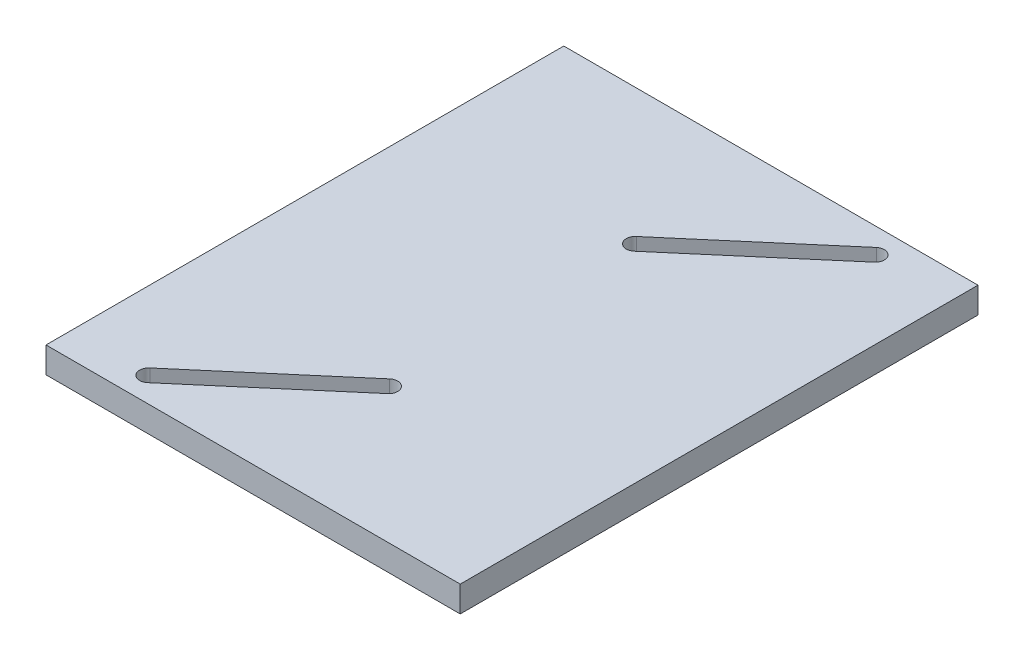
SolidWorks part; units mm, degrees
ref_plane "Front Plane" through (0, 0, 0) normal (0, 0, 1) x (1, 0, 0)
ref_plane "Top Plane" through (0, 0, 0) normal (0, 1, 0) x (1, 0, 0)
ref_plane "Right Plane" through (0, 0, 0) normal (1, 0, 0) x (0, 0, -1)
sketch "Sketch1" plane through (0, 0, 0) normal (0, 1, 0) x (1, 0, 0)
  line L1 (-50.8, -63.5) -> (50.8, -63.5)
  line L2 (-50.8, -63.5) -> (-50.8, 63.5)
  line L3 (-50.8, 63.5) -> (50.8, 63.5)
  line L4 (50.8, -63.5) -> (50.8, 63.5)
  line L5 (-50.8, -63.5) -> (50.8, 63.5) construction
  line L6 (-50.8, 63.5) -> (50.8, -63.5) construction
  point P0 (0, 0)
  dimension "D1" = 127
  dimension "D2" = 101.6
extrude "Boss-Extrude1" add sketch "Sketch1" along normal blind 6.35
sketch "Sketch2" plane through (0, 6.35, 0) normal (0, 1, 0) x (1, 0, 0)
  line L0 (0, 30.2489) -> (31.75, 57.3456) construction
  line L1 (-1.4428, 31.9394) -> (30.3072, 59.0361)
  line L2 (1.4428, 28.5583) -> (33.1928, 55.655)
  line L3 (50.8, 0) -> (-50.8, 0) construction
  line L4 (50.8, -63.5) -> (50.8, 63.5) construction
  line L5 (-50.8, 63.5) -> (-50.8, -63.5) construction
  line L6 (50.8, 63.5) -> (-50.8, 63.5) construction
  line L7 (0, 63.5) -> (0, -63.5) construction
  line L8 (-50.8, -63.5) -> (50.8, -63.5) construction
  line L12 (0, -30.2489) -> (-31.75, -57.3456) construction
  line L13 (1.4428, -31.9394) -> (-30.3072, -59.0361)
  line L14 (-1.4428, -28.5583) -> (-33.1928, -55.655)
  arc A0 (-1.4428, 31.9394) -> (1.4428, 28.5583) centre (0, 30.2489) ccw
  arc A1 (33.1928, 55.655) -> (30.3072, 59.0361) centre (31.75, 57.3456) ccw
  arc A4 (1.4428, -31.9394) -> (-1.4428, -28.5583) centre (0, -30.2489) ccw
  arc A5 (-33.1928, -55.655) -> (-30.3072, -59.0361) centre (-31.75, -57.3456) ccw
  point P2 (15.875, 43.7972)
  point P29 (-15.875, -43.7972)
  dimension "D1" = 30.2489
  dimension "D2" = 31.75
  dimension "D3" = 27.0967
  dimension "D4" = 4.445
extrude "Cut-Extrude1" cut sketch "Sketch2" against normal through all
